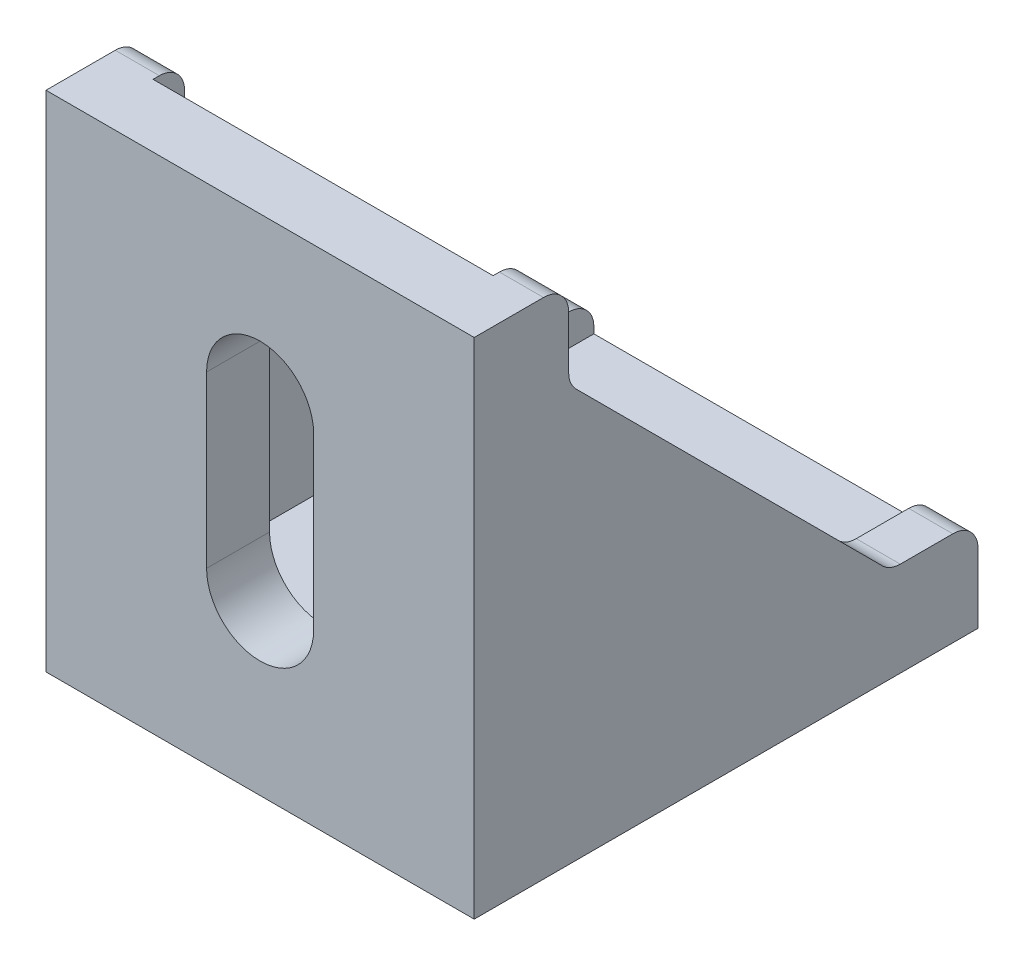
SolidWorks part; units mm, degrees
ref_plane "前视基准面" through (0, 0, 0) normal (0, 0, 1) x (1, 0, 0)
ref_plane "上视基准面" through (0, 0, 0) normal (0, 1, 0) x (1, 0, 0)
ref_plane "右视基准面" through (0, 0, 0) normal (1, 0, 0) x (0, 0, -1)
other "Configuration Table"
sketch "草图1" plane through (0, 0, 0) normal (1, 0, 0) x (0, 0, -1)
  line L0 (0, 0) -> (0, 35)
  line L2 (0, 0) -> (0, -5)
  line L3 (0, -5) -> (40, -5)
  line L4 (40, 0) -> (40, -5)
  line L5 (0, 35) -> (5, 35)
  line L6 (40, 0) -> (5, 0)
  line L7 (5, 0) -> (5, 35)
  dimension "D1" = 35
  dimension "D2" = 5
  dimension "D3" = 40
  dimension "D4" = 5
extrude "凸台-拉伸1" add sketch "草图1" along normal blind 34
sketch "草图2" plane through (34, 0, 0) normal (1, 0, 0) x (0, 0, -1)
  line L0 (40, 0) -> (40, 2.5)
  line L1 (40, 2.5) -> (33, 2.5)
  line L2 (5, 35) -> (7.5, 35)
  line L3 (7.5, 35) -> (7.5, 28)
  line L4 (7.5, 28) -> (33, 2.5)
  line L5 (5, 35) -> (5, 0)
  line L6 (5, 0) -> (40, 0)
  dimension "D1" = 2.5
  dimension "D2" = 7
  dimension "D3" = 2.5
  dimension "D4" = 7
extrude "凸台-拉伸2" add sketch "草图2" against normal blind 3.5
ref_plane "基准面1" through (17, 0, 0) normal (1, 0, 0) x (0, 0, -1)
mirror "镜向1" about plane through (17, 0, 0) normal (1, 0, 0) of "凸台-拉伸2"
sketch "草图4" plane through (0, 0, -5) normal (0, 0, -1) x (-1, 0, 0)
  line L0 (-17, 22) -> (-17, 8.5) construction
  line L1 (-17, 22) -> (-17, -22) construction
  line L2 (-12.75, 22) -> (-12.75, 8.5)
  line L3 (-21.25, 22) -> (-21.25, 8.5)
  line L5 (-30.5, 35) -> (-3.5, 35) construction
  arc A0 (-12.75, 22) -> (-21.25, 22) centre (-17, 22) ccw
  arc A1 (-21.25, 8.5) -> (-12.75, 8.5) centre (-17, 8.5) ccw
  point P4 (-17, 15.25)
  point P11 (-17, 26.25)
  point P12 (-17, 4.25)
  dimension "D1" = 22
  dimension "D2" = 8.5
  dimension "D3" = 13
extrude "切除-拉伸1" cut sketch "草图4" against normal up to next
sketch "草图5" plane through (0, 0, 0) normal (0, 1, 0) x (1, 0, 0)
  line L0 (17, 27) -> (17, 13.5) construction
  line L1 (17, -22) -> (17, 22) construction
  line L2 (21.25, 27) -> (21.25, 13.5)
  line L3 (12.75, 27) -> (12.75, 13.5)
  line L4 (30.5, 40) -> (3.5, 40) construction
  arc A0 (21.25, 27) -> (12.75, 27) centre (17, 27) ccw
  arc A1 (12.75, 13.5) -> (21.25, 13.5) centre (17, 13.5) ccw
  point P4 (17, 20.25)
  point P9 (17, 9.25)
  point P10 (17, 31.25)
  dimension "D1" = 22
  dimension "D2" = 8.5
  dimension "D3" = 13
extrude "切除-拉伸2" cut sketch "草图5" against normal up to next
fillet "圆角1" radius 2 8 edges at (1.75, 28, -7.5) (1.75, 35, -7.5) (32.25, 35, -7.5) (32.25, 28, -7.5) (32.25, 2.5, -33) (1.75, 2.5, -33) (1.75, 2.5, -40) (32.25, 2.5, -40)
